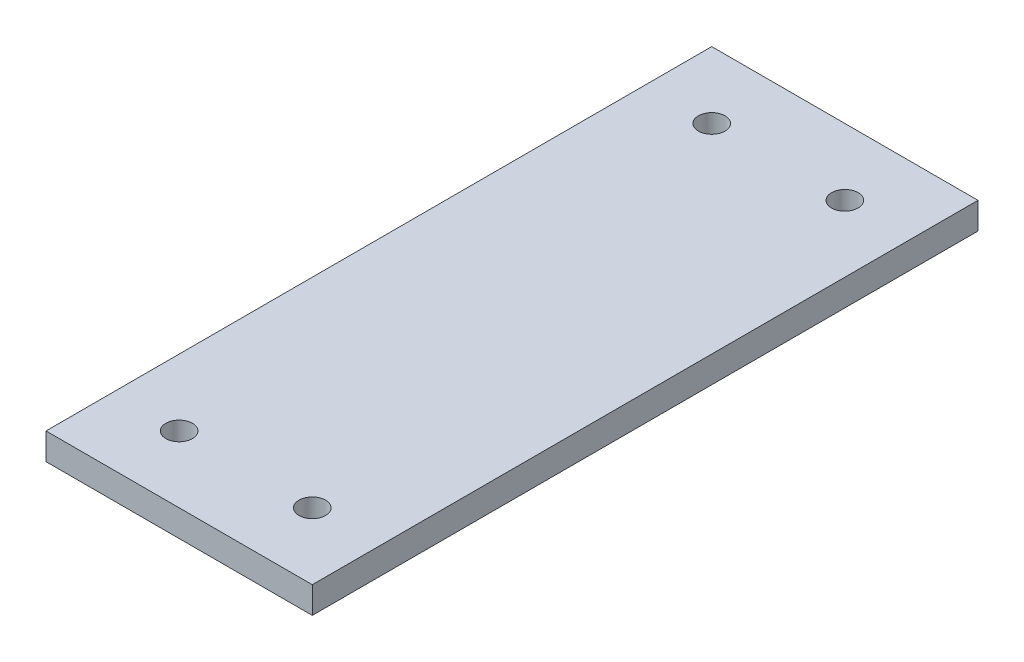
SolidWorks part; units mm, degrees
ref_plane "Plan de face" through (0, 0, 0) normal (0, 0, 1) x (1, 0, 0)
ref_plane "Plan de dessus" through (0, 0, 0) normal (0, 1, 0) x (1, 0, 0)
ref_plane "Plan de droite" through (0, 0, 0) normal (1, 0, 0) x (0, 0, -1)
sketch "Esquisse1" plane through (0, 0, 0) normal (0, 1, 0) x (1, 0, 0)
  line L1 (0, 0) -> (20, 0)
  line L2 (0, 0) -> (0, 50)
  line L3 (0, 50) -> (20, 50)
  line L4 (20, 0) -> (20, 50)
  dimension "D1" = 50
  dimension "D2" = 20
extrude "Boss.-Extru.1" add sketch "Esquisse1" along normal blind 2
sketch "Esquisse2" plane through (0, 2, 0) normal (0, 1, 0) x (1, 0, 0)
  line L0 (0, 50) -> (0, 0) construction
  line L1 (20, 50) -> (0, 50) construction
  line L2 (20, 0) -> (20, 50) construction
  line L3 (0, 0) -> (20, 0) construction
  circle A0 centre (5, 45) radius 1
  circle A1 centre (15, 45) radius 1
  circle A2 centre (15, 5) radius 1
  circle A3 centre (5, 5) radius 1
  dimension "D3" = 2
  dimension "D6" = 2
  dimension "D9" = 2
  dimension "D12" = 2
  dimension "D1" = 5
  dimension "D2" = 5
  dimension "D4" = 5
  dimension "D5" = 5
  dimension "D7" = 5
  dimension "D8" = 5
  dimension "D10" = 5
  dimension "D11" = 5
extrude "Enlèv. mat.-Extru.1" cut sketch "Esquisse2" against normal through all
